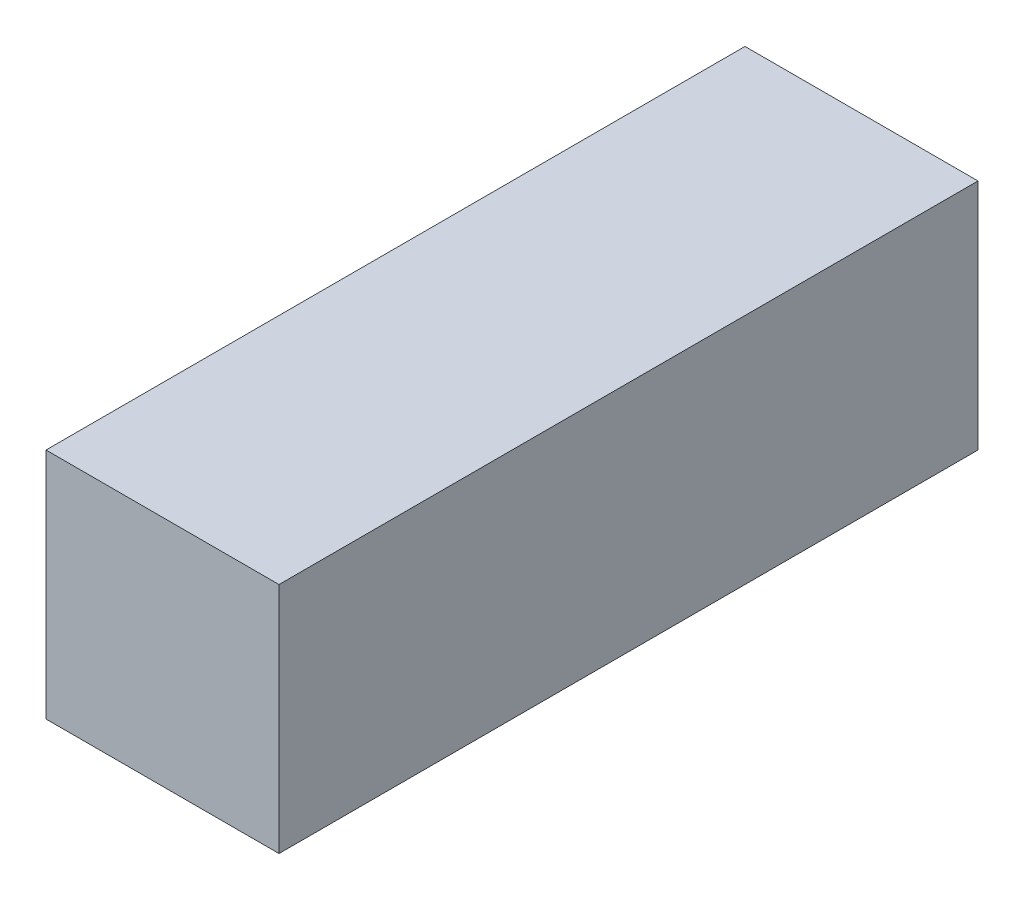
SolidWorks part; units mm, degrees
ref_plane "Front Plane" through (0, 0, 0) normal (0, 0, 1) x (1, 0, 0)
ref_plane "Top Plane" through (0, 0, 0) normal (0, 1, 0) x (1, 0, 0)
ref_plane "Right Plane" through (0, 0, 0) normal (1, 0, 0) x (0, 0, -1)
sketch "Sketch1" plane through (0, 0, 0) normal (0, 0, 1) x (1, 0, 0)
  line L1 (0, 0) -> (20, 0)
  line L2 (0, 0) -> (0, -20)
  line L3 (0, -20) -> (20, -20)
  line L4 (20, 0) -> (20, -20)
  dimension "D1" = 20
  dimension "D2" = 20
extrude "Boss-Extrude1" add sketch "Sketch1" along normal blind 60
sketch "Sketch2" plane through (0, -20, 0) normal (0, -1, 0) x (1, 0, 0)
  line L0 (0, 60) -> (20, 60) construction
  line L1 (20, 60) -> (20, 0) construction
  circle A0 centre (10, 30) radius 2.6
  dimension "D1" = 30
  dimension "D3" = 5.2
  dimension "D2" = 10
extrude "Cut-Extrude1" cut sketch "Sketch2" against normal blind 5
